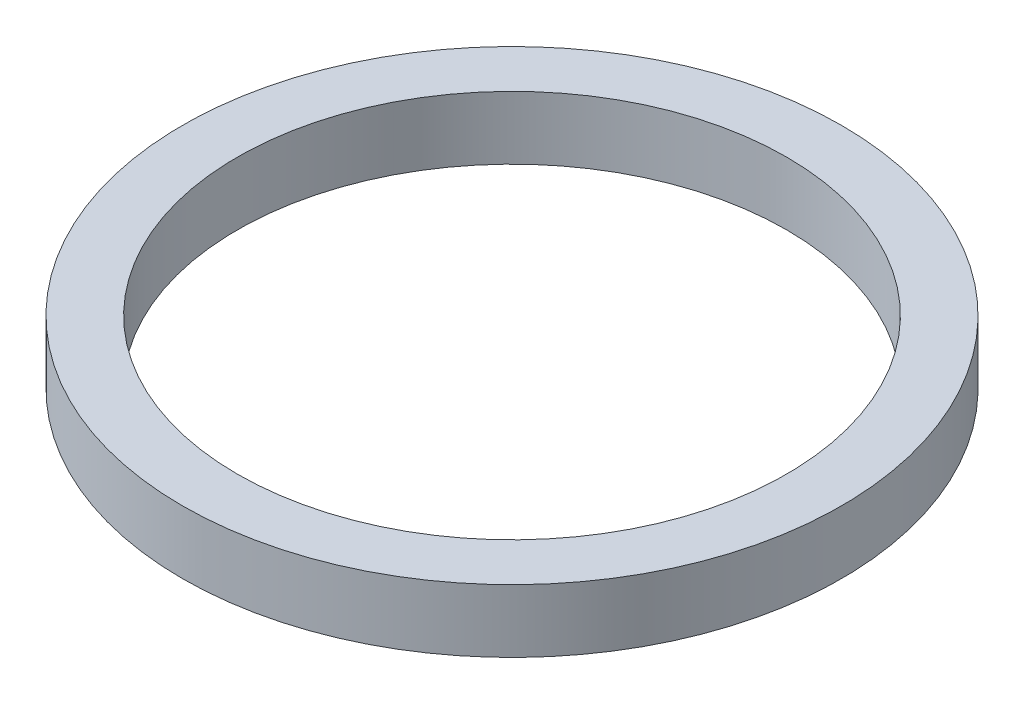
SolidWorks part; units mm, degrees
material "AISI 4130 Steel, normalized at 870C"
ref_plane "Front Plane" through (0, 0, 0) normal (0, 0, 1) x (1, 0, 0)
ref_plane "Top Plane" through (0, 0, 0) normal (0, 1, 0) x (1, 0, 0)
ref_plane "Right Plane" through (0, 0, 0) normal (1, 0, 0) x (0, 0, -1)
sketch "Sketch1" plane through (0, 0, 0) normal (0, 1, 0) x (1, 0, 0)
  circle A0 centre (0, 0) radius 12.5
  circle A1 centre (0, 0) radius 15
  dimension "D1" = 25
  dimension "D2" = 30
extrude "Boss-Extrude1" add sketch "Sketch1" along normal blind 2.87
